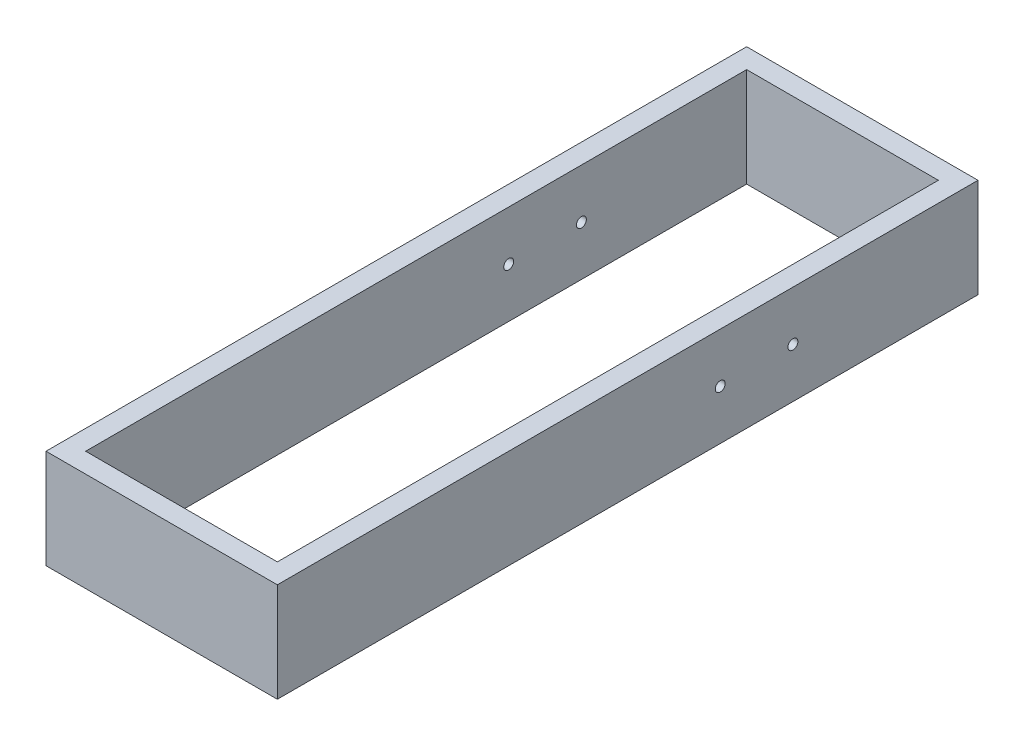
SolidWorks part; units mm, degrees
ref_plane "Front Plane" through (0, 0, 0) normal (0, 0, 1) x (1, 0, 0)
ref_plane "Top Plane" through (0, 0, 0) normal (0, 1, 0) x (1, 0, 0)
ref_plane "Right Plane" through (0, 0, 0) normal (1, 0, 0) x (0, 0, -1)
sketch "Sketch1" plane through (0, 0, 0) normal (0, 1, 0) x (1, 0, 0)
  line L1 (-29, 100) -> (29, 100)
  line L2 (-29, 100) -> (-29, -100)
  line L3 (-29, -100) -> (29, -100)
  line L4 (29, 100) -> (29, -100)
  line L5 (-29, 100) -> (29, -100) construction
  line L6 (-29, -100) -> (29, 100) construction
  line L7 (-35, 106) -> (35, 106)
  line L8 (-35, 106) -> (-35, -106)
  line L9 (-35, -106) -> (35, -106)
  line L10 (35, 106) -> (35, -106)
  line L11 (-35, 106) -> (35, -106) construction
  line L12 (-35, -106) -> (35, 106) construction
  point P0 (0, 0)
  point P6 (0, 0)
  dimension "D1" = 58
  dimension "D2" = 6
  dimension "D3" = 6
  dimension "D4" = 200
extrude "Boss-Extrude1" add sketch "Sketch1" along normal blind 30
sketch "Sketch2" plane through (35, 0, 0) normal (1, 0, 0) x (0, 0, -1)
  line L0 (0, 15) -> (50, 15) construction
  circle A0 centre (50, 15) radius 1.5
  circle A1 centre (28, 15) radius 1.5
  dimension "D2" = 22
  dimension "D1" = 50
extrude "Cut-Extrude1" cut sketch "Sketch2" against normal through all
